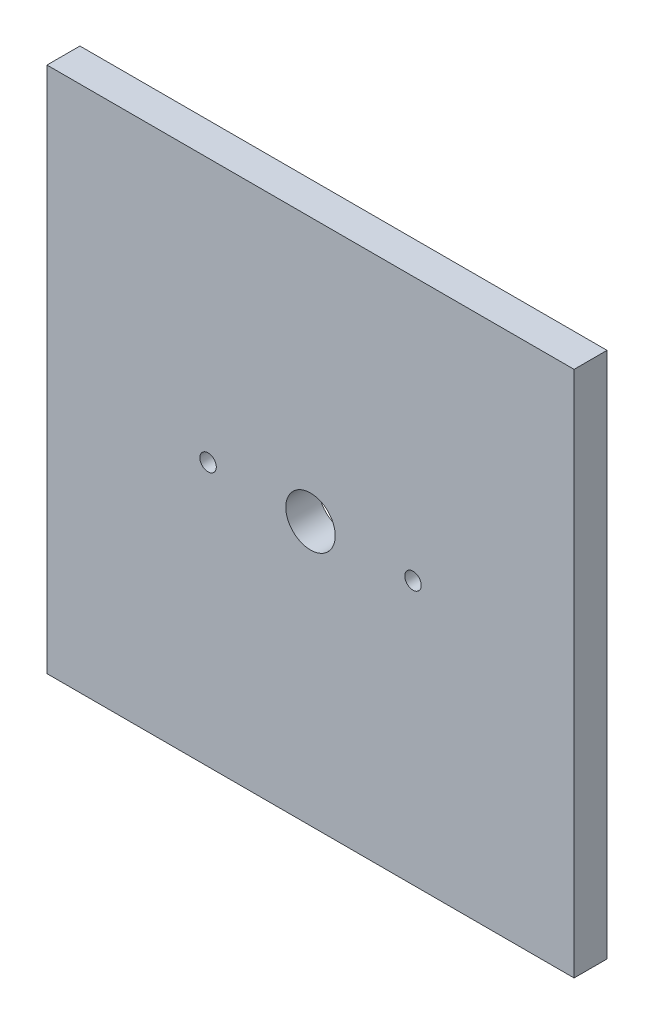
SolidWorks part; units mm, degrees
ref_plane "Front Plane" through (0, 0, 0) normal (0, 0, 1) x (1, 0, 0)
ref_plane "Top Plane" through (0, 0, 0) normal (0, 1, 0) x (1, 0, 0)
ref_plane "Right Plane" through (0, 0, 0) normal (1, 0, 0) x (0, 0, -1)
sketch "Sketch1" plane through (0, 0, 0) normal (0, 0, 1) x (1, 0, 0)
  line L1 (-101.6, 101.6) -> (101.6, 101.6)
  line L2 (-101.6, 101.6) -> (-101.6, -101.6)
  line L3 (-101.6, -101.6) -> (101.6, -101.6)
  line L4 (101.6, 101.6) -> (101.6, -101.6)
  line L5 (-101.6, 101.6) -> (101.6, -101.6) construction
  line L6 (-101.6, -101.6) -> (101.6, 101.6) construction
  point P0 (0, 0)
  dimension "D1" = 203.2
  dimension "D2" = 203.2
extrude "Boss-Extrude1" add sketch "Sketch1" along normal blind 12.7
sketch "Sketch2" plane through (0, 0, 12.7) normal (0, 0, 1) x (1, 0, 0)
  line L0 (101.6, 101.6) -> (-101.6, 101.6) construction
  circle A0 centre (0, 0) radius 9.525
  circle A1 centre (39.497, 0) radius 3.175
  circle A2 centre (-39.497, 0) radius 3.175
  point P7 (0, 0)
  point P8 (0, 0)
  point P9 (0, 0)
  dimension "D1" = 19.05
  dimension "D2" = 6.35
  dimension "D3" = 6.35
  dimension "D4" = 78.994
  dimension "D5" = 39.497
  dimension "D6" = 101.6
  dimension "D7" = 101.6
extrude "Cut-Extrude1" cut sketch "Sketch2" against normal through all
